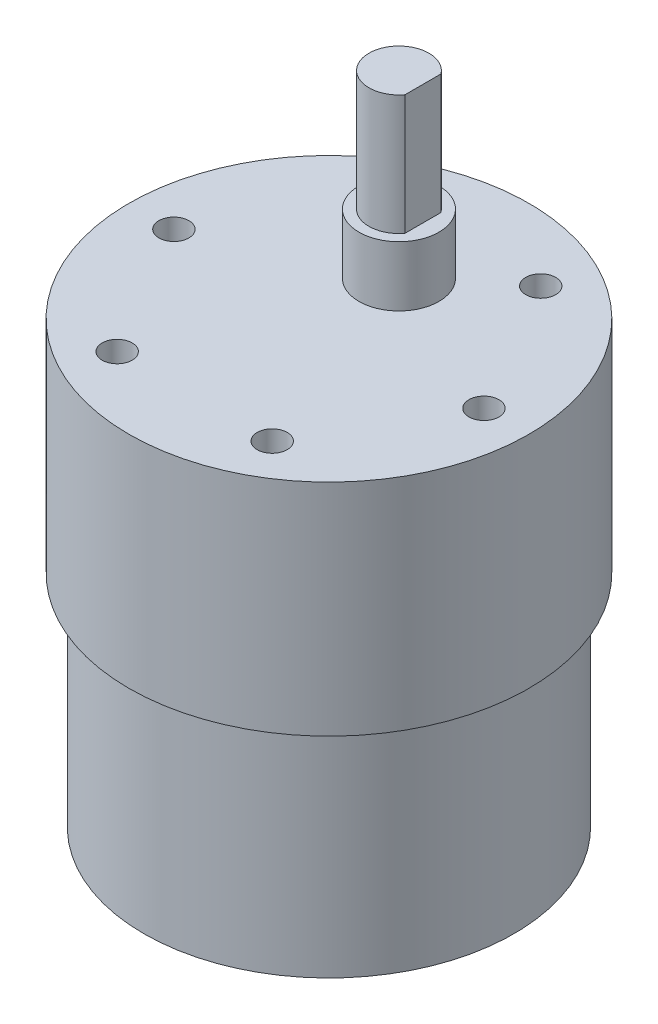
SolidWorks part; units mm, degrees
ref_plane "前视基准面" through (0, 0, 0) normal (0, 0, 1) x (1, 0, 0)
ref_plane "上视基准面" through (0, 0, 0) normal (0, 1, 0) x (1, 0, 0)
ref_plane "右视基准面" through (0, 0, 0) normal (1, 0, 0) x (0, 0, -1)
sketch "草图1" plane through (0, 0, 0) normal (0, 1, 0) x (1, 0, 0)
  circle A0 centre (0, 0) radius 18.5
  dimension "D1" = 37
extrude "凸台-拉伸1" add sketch "草图1" along normal blind 22
sketch "草图2" plane through (0, 22, 0) normal (0, 1, 0) x (1, 0, 0)
  circle A0 centre (0, 0) radius 20
  dimension "D1" = 40
extrude "凸台-拉伸2" add sketch "草图2" along normal blind 22
sketch "草图3" plane through (0, 44, 0) normal (0, 1, 0) x (1, 0, 0)
  line L0 (-7.75, 13.4234) -> (7.75, 13.4234) construction
  line L1 (7.75, 13.4234) -> (15.5, 0) construction
  line L2 (15.5, 0) -> (7.75, -13.4234) construction
  line L3 (7.75, -13.4234) -> (-7.75, -13.4234) construction
  line L4 (-7.75, -13.4234) -> (-15.5, 0) construction
  line L5 (-15.5, 0) -> (-7.75, 13.4234) construction
  circle A7 centre (0, 0) radius 15.5 construction
  circle A8 centre (-7.75, 13.4234) radius 1.5
  circle A9 centre (-15.5, 0) radius 1.5
  circle A10 centre (-7.75, -13.4234) radius 1.5
  circle A11 centre (7.75, -13.4234) radius 1.5
  circle A12 centre (15.5, 0) radius 1.5
  circle A13 centre (7.75, 13.4234) radius 1.5
  dimension "D1" = 3
  dimension "D2" = 31
extrude "切除-拉伸1" cut sketch "草图3" against normal blind 5
sketch "草图4" plane through (0, 44, 0) normal (0, 1, 0) x (1, 0, 0)
  circle A0 centre (0, 7) radius 4
  dimension "D1" = 8
  dimension "D2" = 7
extrude "凸台-拉伸3" add sketch "草图4" along normal blind 6
sketch "草图5" plane through (0, 50, 0) normal (0, 1, 0) x (1, 0, 0)
  line L0 (2.4, 8.8) -> (2.4, 5.2)
  line L1 (-3, 7) -> (-3, 1.3282) construction
  arc A0 (2.4, 8.8) -> (2.4, 5.2) centre (0, 7) ccw
  point P5 (2.4, 7)
  dimension "D1" = 6
  dimension "D2" = 5.4
extrude "凸台-拉伸4" add sketch "草图5" along normal blind 12
